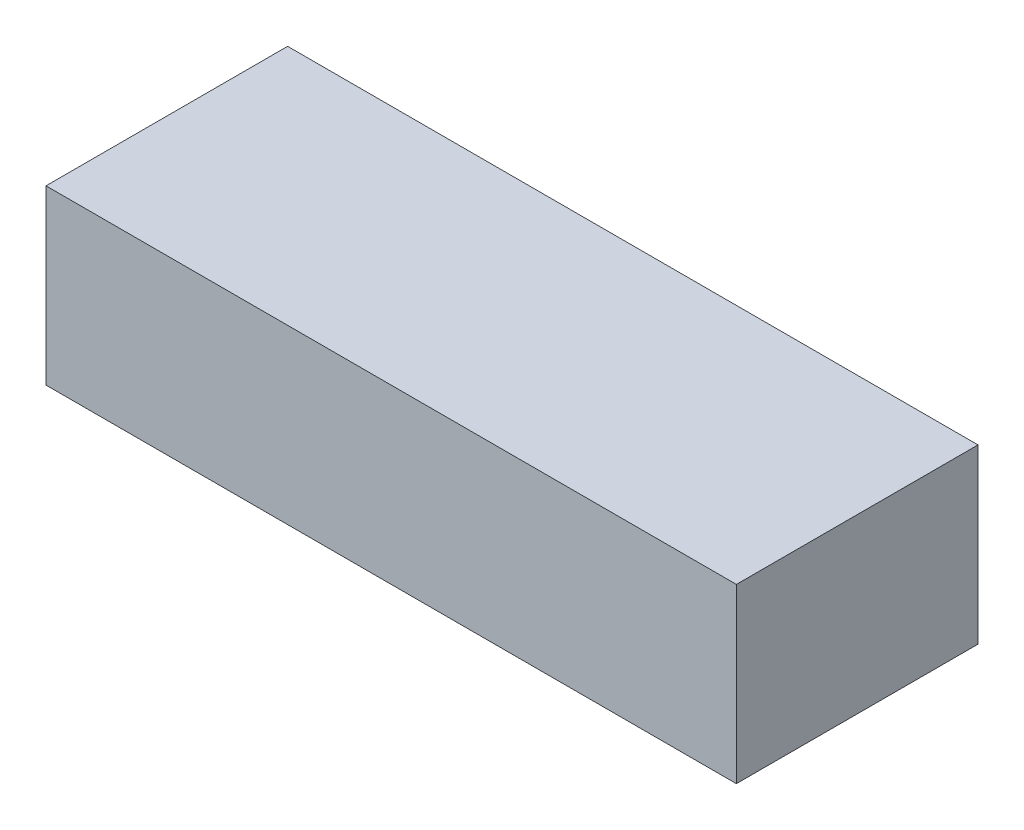
SolidWorks part; units mm, degrees
material "Acrylic (Medium-high impact)"
ref_plane "Front Plane" through (0, 0, 0) normal (0, 0, 1) x (1, 0, 0)
ref_plane "Top Plane" through (0, 0, 0) normal (0, 1, 0) x (1, 0, 0)
ref_plane "Right Plane" through (0, 0, 0) normal (1, 0, 0) x (0, 0, -1)
sketch "Sketch1" plane through (0, 0, 0) normal (0, 1, 0) x (1, 0, 0)
  line L1 (-100, 35) -> (100, 35)
  line L2 (-100, 35) -> (-100, -35)
  line L3 (-100, -35) -> (100, -35)
  line L4 (100, 35) -> (100, -35)
  line L5 (-100, 35) -> (100, -35) construction
  line L6 (-100, -35) -> (100, 35) construction
  point P0 (0, 0)
extrude "Boss-Extrude1" add sketch "Sketch1" along normal blind 50
